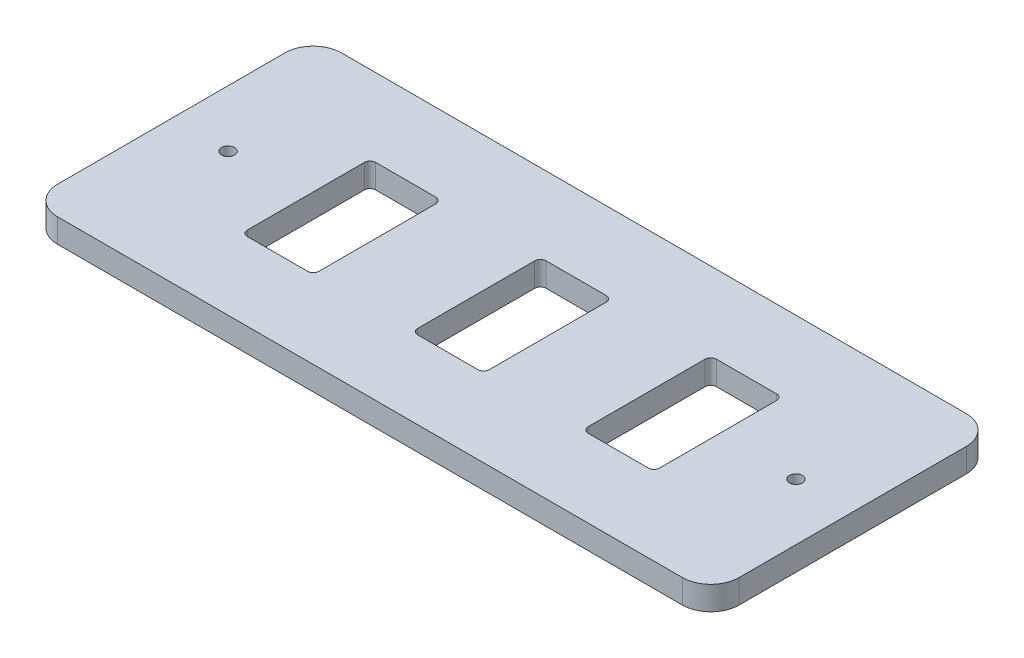
SolidWorks part; units mm, degrees
ref_plane "Front" through (0, 0, 0) normal (0, 0, 1) x (1, 0, 0)
ref_plane "Top" through (0, 0, 0) normal (0, 1, 0) x (1, 0, 0)
ref_plane "Right" through (0, 0, 0) normal (1, 0, 0) x (0, 0, -1)
sketch "Sketch1" plane through (0, 0, 0) normal (0, 1, 0) x (1, 0, 0)
  line L0 (0, 0) -> (0, -53.1859) construction
  line L1 (-76.2, 31.75) -> (76.2, 31.75)
  line L2 (-76.2, 31.75) -> (-76.2, -31.75)
  line L3 (-76.2, -31.75) -> (76.2, -31.75)
  line L4 (76.2, 31.75) -> (76.2, -31.75)
  line L5 (-76.2, 31.75) -> (76.2, -31.75) construction
  line L6 (-76.2, -31.75) -> (76.2, 31.75) construction
  line L7 (-46.101, 14.351) -> (-30.099, 14.351)
  line L8 (-46.101, 14.351) -> (-46.101, -14.351)
  line L9 (-46.101, -14.351) -> (-30.099, -14.351)
  line L10 (-30.099, 14.351) -> (-30.099, -14.351)
  line L11 (-46.101, 14.351) -> (-30.099, -14.351) construction
  line L12 (-46.101, -14.351) -> (-30.099, 14.351) construction
  line L13 (-8.001, 14.351) -> (8.001, 14.351)
  line L14 (-8.001, 14.351) -> (-8.001, -14.351)
  line L15 (-8.001, -14.351) -> (8.001, -14.351)
  line L16 (8.001, 14.351) -> (8.001, -14.351)
  line L17 (-8.001, 14.351) -> (8.001, -14.351) construction
  line L18 (-8.001, -14.351) -> (8.001, 14.351) construction
  line L19 (30.099, 14.351) -> (46.101, 14.351)
  line L20 (30.099, 14.351) -> (30.099, -14.351)
  line L21 (30.099, -14.351) -> (46.101, -14.351)
  line L22 (46.101, 14.351) -> (46.101, -14.351)
  line L23 (30.099, 14.351) -> (46.101, -14.351) construction
  line L24 (30.099, -14.351) -> (46.101, 14.351) construction
  circle A0 centre (63.5, 0) radius 1.4605
  circle A1 centre (-63.5, 0) radius 1.4605
  point P0 (0, 0)
  point P6 (-38.1, 0)
  point P11 (0, 0)
  point P16 (38.1, 0)
  dimension "D7" = 2.921
  dimension "D1" = 38.1
  dimension "D2" = 16.002
  dimension "D3" = 28.702
  dimension "D4" = 38.1
  dimension "D5" = 63.5
  dimension "D6" = 152.4
  dimension "D8" = 63.5
extrude "Boss-Extrude1" add sketch "Sketch1" along normal mid plane 5.334
fillet "Fillet1" radius 1.27 12 edges at (30.099, 0, 14.351) (46.101, 0, -14.351) (30.099, 0, -14.351) (46.101, 0, 14.351) (8.001, 0, 14.351) (-8.001, 0, 14.351) (8.001, 0, -14.351) (-8.001, 0, -14.351) (-46.101, 0, -14.351) (-30.099, 0, -14.351) (-46.101, 0, 14.351) (-30.099, 0, 14.351)
fillet "Fillet2" radius 6.35 4 edges at (-76.2, 0, -31.75) (76.2, 0, -31.75) (76.2, 0, 31.75) (-76.2, 0, 31.75)
